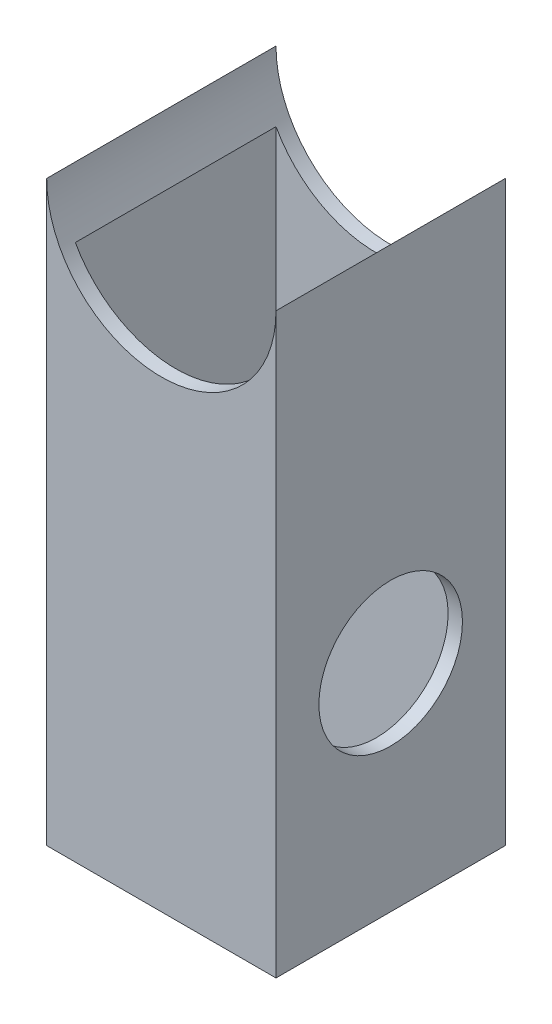
SolidWorks part; units mm, degrees
ref_plane "Front Plane" through (0, 0, 0) normal (0, 0, 1) x (1, 0, 0)
ref_plane "Top Plane" through (0, 0, 0) normal (0, 1, 0) x (1, 0, 0)
ref_plane "Right Plane" through (0, 0, 0) normal (1, 0, 0) x (0, 0, -1)
sketch "Sketch1" plane through (0, 0, 0) normal (0, 1, 0) x (1, 0, 0)
  line L0 (11.1125, 11.1125) -> (-11.1125, 11.1125)
  line L1 (12.7, 12.7) -> (-12.7, 12.7)
  line L2 (-12.7, 12.7) -> (-12.7, -12.7)
  line L3 (-12.7, -12.7) -> (12.7, -12.7)
  line L4 (12.7, -12.7) -> (12.7, 12.7)
  line L5 (-11.1125, 11.1125) -> (-11.1125, -11.1125)
  line L6 (-11.1125, -11.1125) -> (11.1125, -11.1125)
  line L7 (11.1125, -11.1125) -> (11.1125, 11.1125)
  circle A0 centre (0, 0) radius 12.7 construction
  circle A1 centre (0, 0) radius 11.1125 construction
  point P13 (-12.7, 12.7)
  point P14 (10.2552, 15.1448)
  point P15 (11.4806, 13.9194)
  dimension "D1" = 25.4
  dimension "D2" = 1.5875
extrude "Boss-Extrude1" add sketch "Sketch1" along normal up to vertex (63.999 mm away)
sketch "Sketch2" plane through (0, 0, 12.7) normal (0, 0, 1) x (1, 0, 0)
  line L0 (-12.7, 63.999) -> (12.7, 63.999) construction
  circle A0 centre (0, 63.999) radius 12.7
extrude "Cut-Extrude1" cut sketch "Sketch2" against normal through all
sketch "Sketch3" plane through (12.7, 0, 0) normal (1, 0, 0) x (0, 0, -1)
  line L0 (0, 63.999) -> (0, 0) construction
  line L1 (-12.7, 63.999) -> (12.7, 63.999) construction
  circle A0 centre (0, 23.8506) radius 7.9502
  dimension "D1" = 15.9004
  dimension "D2" = 23.8506
extrude "Cut-Extrude2" cut sketch "Sketch3" against normal through all
sketch "Sketch4" plane through (12.7, 0, 0) normal (1, 0, 0) x (0, 0, -1)
  line L0 (0, 63.999) -> (0, 0) construction
  line L1 (-12.7, 63.999) -> (12.7, 63.999) construction
sketch3d "3DSketch3"
  line L0 (38.1087, 23.8506, 0) -> (-28.5664, 23.8506, 0) construction
  line L1 (12.7, 63.999, 0) -> (12.7, 0, 0) construction
  line L2 (12.7, 0, 12.7) -> (12.7, 0, -12.7) construction
  line L3 (-12.7, 63.999, 0) -> (12.7, 63.999, 0) construction
  line L4 (-12.7, 63.999, -12.7) -> (-12.7, 63.999, 12.7) construction
  point P0 (38.1087, 23.8506, 0)
  point P1 (-28.5664, 23.8506, 0)
sketch "Sketch5" plane through (0, 0, 0) normal (0, 0, 1) x (1, 0, 0)
  line L0 (0, 0) -> (0, 63.999) construction
  line L1 (-12.7, 63.999) -> (12.7, 63.999) construction
equation "\"diameter\"= .626"
equation "\"D1@Sketch3\"=\"diameter\""
equation "\"D2@Sketch3\"=\"diameter\"*1.5"
equation "\"D1@Boss-Extrude1\"=2*\"diameter\"+1.03+.5-(\"diameter\"-.5)/2"
